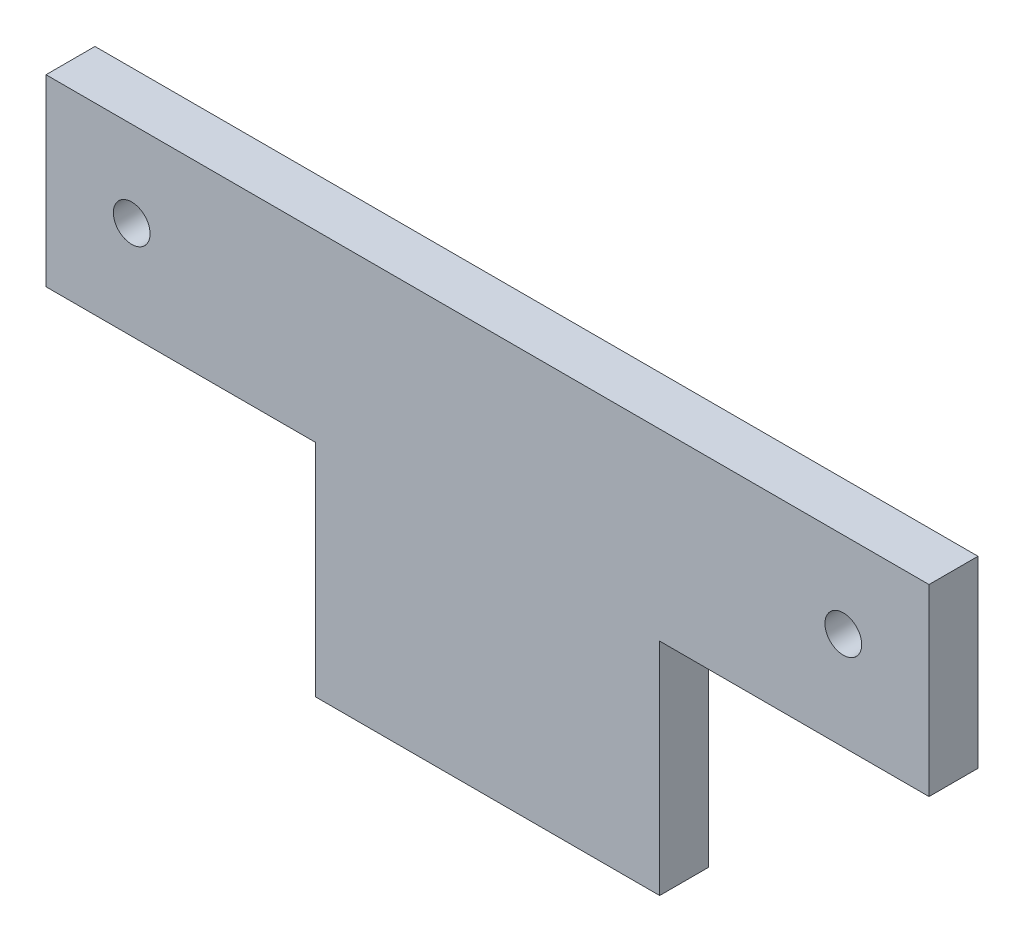
SolidWorks part; units mm, degrees
ref_plane "前视基准面" through (0, 0, 0) normal (0, 0, 1) x (1, 0, 0)
ref_plane "上视基准面" through (0, 0, 0) normal (0, 1, 0) x (1, 0, 0)
ref_plane "右视基准面" through (0, 0, 0) normal (1, 0, 0) x (0, 0, -1)
sketch "草图1" plane through (0, 0, 0) normal (0, 0, 1) x (1, 0, 0)
  line L0 (0, 0) -> (58.12, 0) construction
  line L9 (-7, 7) -> (65.12, 7)
  line L10 (65.12, 7) -> (65.12, -8)
  line L11 (65.12, -8) -> (43.12, -8)
  line L12 (43.12, -8) -> (43.12, -26)
  line L13 (43.12, -26) -> (15, -26)
  line L14 (15, -26) -> (15, -8)
  line L15 (15, -8) -> (-7, -8)
  line L16 (-7, -8) -> (-7, 7)
  circle A0 centre (0, 0) radius 1.5
  circle A1 centre (58.12, 0) radius 1.5
  dimension "D1" = 7
  dimension "D5" = 15
  dimension "D2" = 58.12
  dimension "D3" = 7
  dimension "D4" = 22
  dimension "D6" = 7
extrude "凸台-拉伸1" add sketch "草图1" along normal blind 4
